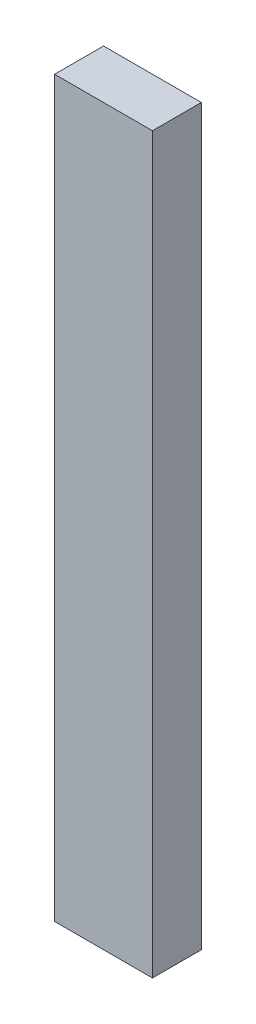
SolidWorks part; units mm, degrees
ref_plane "Front Plane" through (0, 0, 0) normal (0, 0, 1) x (1, 0, 0)
ref_plane "Top Plane" through (0, 0, 0) normal (0, 1, 0) x (1, 0, 0)
ref_plane "Right Plane" through (0, 0, 0) normal (1, 0, 0) x (0, 0, -1)
sketch "Sketch1" plane through (0, 0, 0) normal (0, 1, 0) x (1, 0, 0)
  line L1 (-10, 5) -> (10, 5)
  line L2 (-10, 5) -> (-10, -5)
  line L3 (-10, -5) -> (10, -5)
  line L4 (10, 5) -> (10, -5)
  line L5 (-10, 5) -> (10, -5) construction
  line L6 (-10, -5) -> (10, 5) construction
  point P0 (0, 0)
  dimension "D1" = 10
  dimension "D2" = 20
extrude "Boss-Extrude1" add sketch "Sketch1" along normal blind 150
